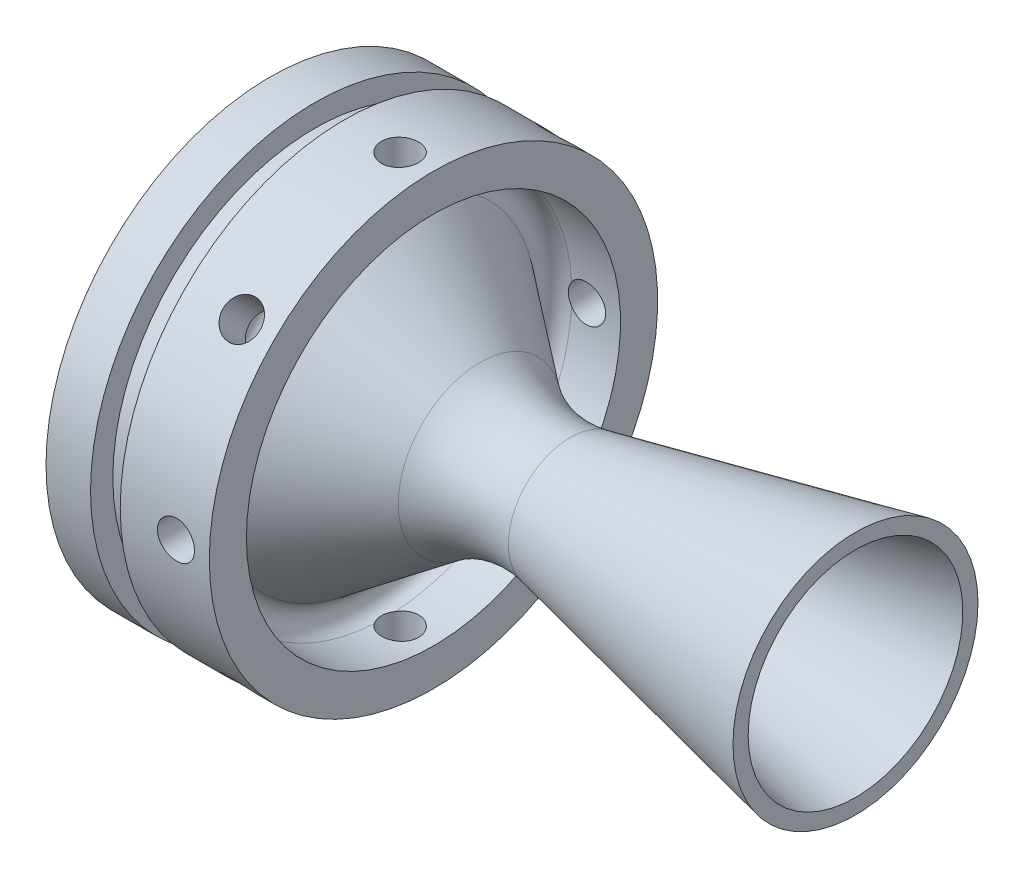
SolidWorks part; units mm, degrees
ref_plane "Front Plane" through (0, 0, 0) normal (0, 0, 1) x (1, 0, 0)
ref_plane "Top Plane" through (0, 0, 0) normal (0, 1, 0) x (1, 0, 0)
ref_plane "Right Plane" through (0, 0, 0) normal (1, 0, 0) x (0, 0, -1)
sketch "Sketch1" plane through (0, 0, 0) normal (0, 0, 1) x (1, 0, 0)
  line L0 (-34.3623, 0) -> (66.4867, 0) construction
  line L2 (1.0396, 4.8293) -> (46.3486, 14.46)
  line L3 (46.3486, 14.46) -> (46.3486, 16.5047)
  line L4 (0, -46.2093) -> (0, 57.6473) construction
  line L6 (-22.5049, 30.2) -> (-10.5049, 30.2)
  line L9 (-3.0091, 5.7268) -> (-32.5049, 27.9535)
  line L10 (-48.4934, 30.2) -> (-22.3285, 30.2) construction
  line L11 (-32.5049, 27.9535) -> (-32.5049, 30.2)
  line L12 (-32.5049, 30.2) -> (-26.5049, 30.2)
  line L14 (-10.5049, 30.2) -> (-10.5049, 25.2)
  line L16 (-26.5049, 30.2) -> (-26.5049, 27.2)
  line L17 (-26.5049, 27.2) -> (-22.5049, 27.2)
  line L18 (-22.5049, 30.2) -> (-22.5049, 27.2)
  line L19 (-18.2614, 21.6027) -> (-4.2289, 11.0285)
  line L20 (7.917, 8.3358) -> (46.3486, 16.5047)
  line L21 (-10.5049, 25.2) -> (-17.0577, 25.2)
  arc A0 (-17.0577, 25.2) -> (-18.2614, 21.6027) centre (-17.0577, 23.2) ccw
  arc A1 (-4.2289, 11.0285) -> (7.917, 8.3358) centre (4.7984, 23.008) ccw
  arc A2 (-3.0091, 5.7268) -> (1.0396, 4.8293) centre (0, 9.72) ccw
  point P11 (0, 4.72)
  dimension "D14" = 37
  dimension "D16" = 2
  dimension "D10" = 15
  dimension "D6" = 5
  dimension "D2" = 4.72
  dimension "D3" = 3.5
  dimension "D4" = 14.46
  dimension "D5" = 12
  dimension "D7" = 30.2
  dimension "D8" = 5
  dimension "D9" = 2
  dimension "D11" = 10.5049
  dimension "D12" = 4
  dimension "D13" = 3
  dimension "D17" = 12
  dimension "D18" = 6
revolve "Revolve1" add sketch "Sketch1" angle 360 about L0
fillet "Fillet1" [suppressed] radius 5
fillet "Fillet2" [suppressed] radius 3
ref_axis "Axis1" through (-42.8963, 0, 0) along (1, 0, 0)
ref_plane "Plane1" through (0, 22, 0) normal (0, 1, 0) x (-1, 0, 0)
sketch "Sketch4" plane through (0, 22, 0) normal (0, 1, 0) x (-1, 0, 0)
  line L0 (42.8963, 0) -> (-48.4732, 0) construction
  circle A0 centre (15, 0) radius 2.5
  dimension "D1" = 5
  dimension "D2" = 15
extrude "Cut-Extrude2" cut sketch "Sketch4" along normal blind 100
pattern_circular "CirPattern2" count 8 over 360 about axis through (-42.8963, 0, 0) along (1, 0, 0) of "Cut-Extrude2"
